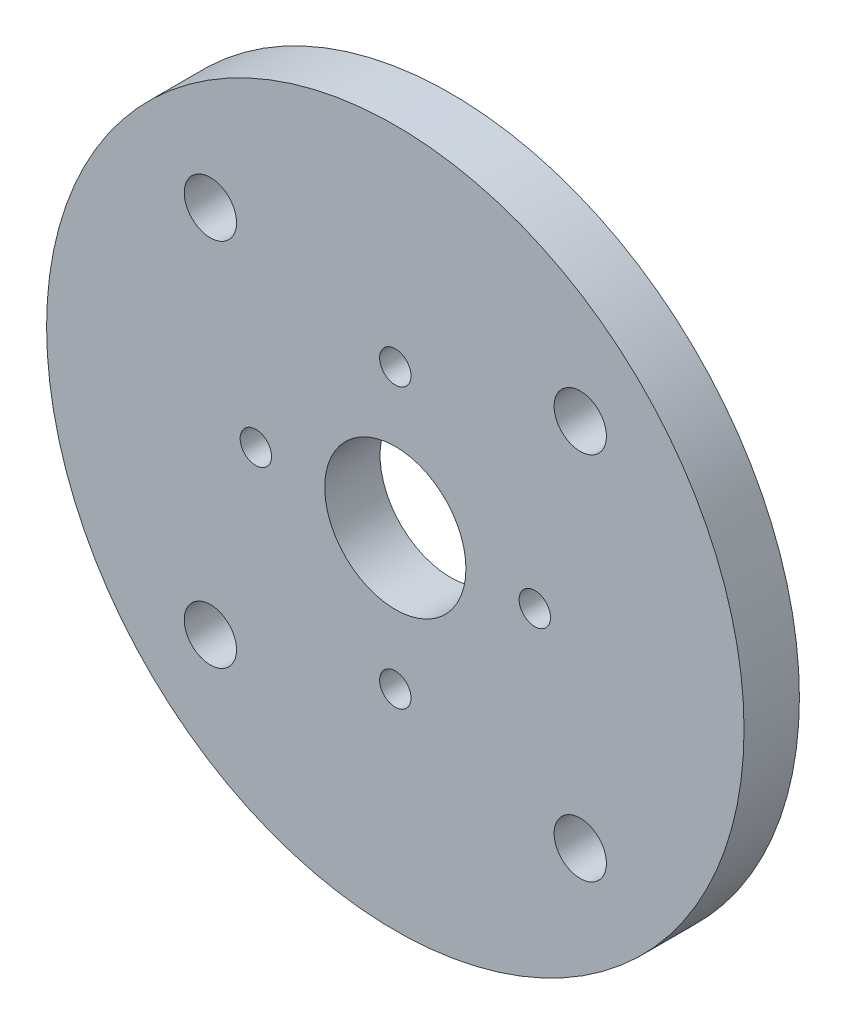
SolidWorks part; units mm, degrees
ref_plane "Plan de face" through (0, 0, 0) normal (0, 0, 1) x (1, 0, 0)
ref_plane "Plan de dessus" through (0, 0, 0) normal (0, 1, 0) x (1, 0, 0)
ref_plane "Plan de droite" through (0, 0, 0) normal (1, 0, 0) x (0, 0, -1)
sketch "Esquisse1" plane through (0, 0, 0) normal (0, 0, 1) x (1, 0, 0)
  circle A0 centre (0, 0) radius 20
  dimension "D1" = 40
extrude "Boss.-Extru.1" add sketch "Esquisse1" along normal blind 3.175
sketch "Esquisse2" plane through (0, 0, 3.175) normal (0, 0, 1) x (1, 0, 0)
  line L0 (0, 0) -> (0, 8) construction
  line L1 (-8, 0) -> (0, 0) construction
  circle A0 centre (0, 0) radius 4.05
  circle A1 centre (0, 0) radius 8 construction
  circle A2 centre (0, 8) radius 0.9
  circle A3 centre (8, 0) radius 0.9
  circle A4 centre (0, -8) radius 0.9
  circle A5 centre (-8, 0) radius 0.9
  point P15 (0, 0)
  dimension "D1" = 8.1
  dimension "D2" = 16
  dimension "D3" = 1.8
  dimension "D4" = 4
extrude "Enlèv. mat.-Extru.1" cut sketch "Esquisse2" against normal through all
sketch "Esquisse3" plane through (0, 0, 3.175) normal (0, 0, 1) x (1, 0, 0)
  line L0 (0, 0) -> (10.6066, 10.6066) construction
  line L1 (0, 0) -> (0, 15) construction
  circle A0 centre (0, 0) radius 15 construction
  circle A1 centre (10.6066, 10.6066) radius 1.5
  circle A2 centre (10.6066, -10.6066) radius 1.5
  circle A3 centre (-10.6066, -10.6066) radius 1.5
  circle A4 centre (-10.6066, 10.6066) radius 1.5
  point P6 (-11.3837, -9.7679)
  point P7 (-10.6039, 10.6093)
  point P15 (0, 0)
  dimension "D2" = 3
  dimension "D3" = 30
  dimension "D1" = 45
  dimension "D4" = 4
extrude "Enlèv. mat.-Extru.2" cut sketch "Esquisse3" against normal through all and the other way through all
